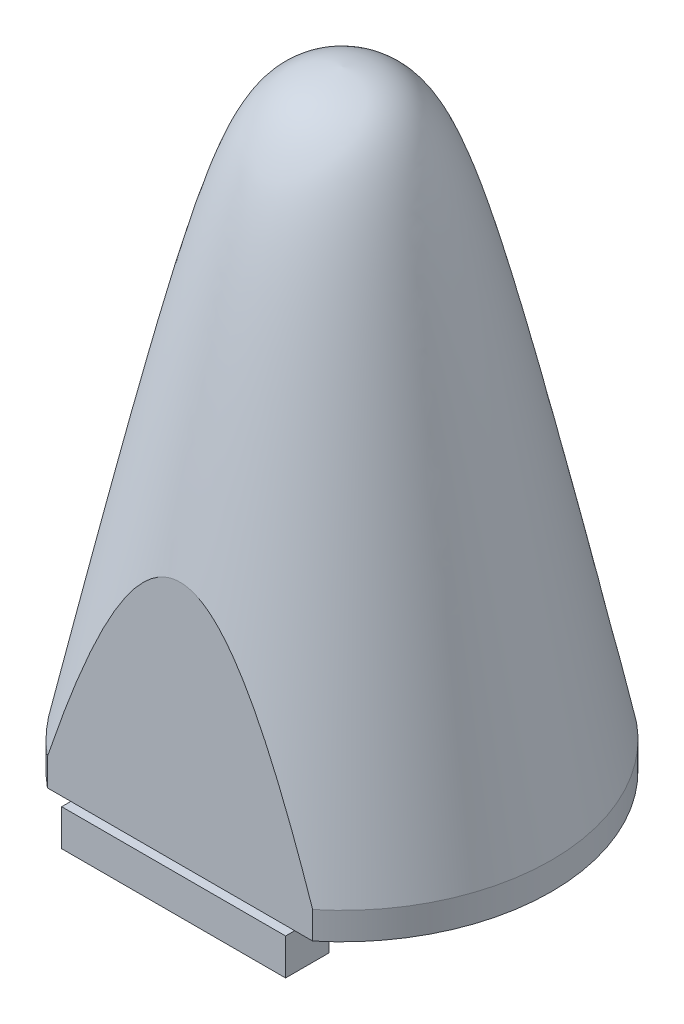
SolidWorks part; units mm, degrees
ref_plane "前视基准面" through (0, 0, 0) normal (0, 0, 1) x (1, 0, 0)
ref_plane "上视基准面" through (0, 0, 0) normal (0, 1, 0) x (1, 0, 0)
ref_plane "右视基准面" through (0, 0, 0) normal (1, 0, 0) x (0, 0, -1)
sketch "草图2" plane through (0, 0, 0) normal (0, 0, 1) x (1, 0, 0)
  line L1 (0, 0) -> (-11.5, 0)
  line L2 (0, 0) -> (0, 32)
  conic Q0 (0, 32) -> (-11.5, 0) control (-4.7103, 31.6151) rho 0.718414
  dimension "D1" = 11.5
  dimension "D2" = 32
revolve "旋转1" add sketch "草图2" angle 360 about L2
sketch "草图3" plane through (0, 0, 0) normal (0, 0, 1) x (1, 0, 0)
  line L0 (0, 31) -> (0, 0)
  line L1 (-11.5, 0) -> (11.5, 0) construction
  line L2 (0, 0) -> (-8, 0)
  line L3 (-8, 0) -> (0, 31)
  point P5 (-8, 0)
  point P8 (0, 31)
  dimension "D1" = 8
  dimension "D2" = 31
revolve "切除-旋转1" cut sketch "草图3" angle 360 about L0
sketch "草图4" plane through (0, 0, 0) normal (0, 1, 0) x (1, 0, 0)
  circle A0 centre (0, 0) radius 11.5
  dimension "D1" = 23
extrude "凸台-拉伸1" add sketch "草图4" against normal blind 1.5
sketch "草图5" plane through (0, -1.5, 0) normal (0, -1, 0) x (1, 0, 0)
  line L0 (-9.6096, 0) -> (10.8151, 0) construction
  line L9 (-7.6853, -7.4312) -> (8.2673, 7.9939) construction
  line L10 (4.3011, 6.4) -> (4.3011, 5.02)
  line L11 (-8, -6.4) -> (-8, 6.4)
  line L12 (-8, 6.4) -> (-6.6189, 6.4)
  line L14 (-6.6189, -6.4) -> (-8, -6.4)
  line L15 (-6.6189, 6.4) -> (4.3011, 6.4)
  line L16 (0, 0) -> (6.5976, -7.5148) construction
  line L17 (4.3011, 5.02) -> (-6.5, 5.02)
  line L18 (-6.5, 5.02) -> (-6.5, -5.02)
  line L19 (4.3011, -6.4) -> (4.3011, -5.02)
  line L20 (4.3011, -5.02) -> (-6.5, -5.02)
  line L21 (-6.6189, -6.4) -> (4.3011, -6.4)
  circle A1 centre (0, 0) radius 11.5 construction
  point P0 (0, 0)
  point P1 (0, 0)
  point P14 (-8, 0)
  point P23 (-6.5, 0)
  dimension "D1" = 6.4
  dimension "D2" = 8
  dimension "D3" = 10.92
  dimension "D4" = 1.38
  dimension "D5" = 1.5
extrude "凸台-拉伸2" add sketch "草图5" along normal blind 4
sketch "草图8" plane through (0, -1.5, 0) normal (0, -1, 0) x (-1, 0, 0)
  line L0 (10.5002, -4.69) -> (10.5002, 4.69)
  line L1 (7.285, -8.8982) -> (-7.285, -8.8982)
  line L2 (0, 0) -> (-4.2231, 0) construction
  line L5 (7.285, 8.8982) -> (-7.285, 8.8982)
  circle A0 centre (0, 0) radius 11.5 construction
  arc A2 (-7.285, -8.8982) -> (7.285, -8.8982) centre (0, 0) ccw
  arc A3 (10.5002, 4.69) -> (10.5002, -4.69) centre (0, 0) cw
  arc A5 (-7.285, 8.8982) -> (7.285, 8.8982) centre (0, 0) cw
  dimension "D1" = 9.38
  dimension "D2" = 14.57
sketch "草图6" plane through (0, -1.5, 0) normal (0, -1, 0) x (1, 0, 0)
  line L1 (0, 0) -> (11.7815, 0) construction
sketch "草图7" plane through (0, -1.5, 0) normal (0, -1, 0) x (1, 0, 0)
  line L1 (6.5, -5.02) -> (-6.5, -5.02)
  line L2 (6.5, -5.02) -> (6.5, 5.02)
  line L3 (6.5, 5.02) -> (-6.5, 5.02)
  line L4 (-6.5, -5.02) -> (-6.5, 5.02)
  line L5 (6.5, -5.02) -> (-6.5, 5.02) construction
  line L6 (6.5, 5.02) -> (-6.5, -5.02) construction
  point P0 (0, 0)
extrude "切除-拉伸3" cut sketch "草图7" against normal blind 2
extrude "切除-拉伸4" cut sketch "草图8" against normal through all
sketch "草图9" plane through (0, 0, 6.4) normal (0, 0, 1) x (1, 0, 0)
  line L0 (4.3011, -5.5) -> (4.3011, -1.5) construction
  line L1 (-8, -5.5) -> (4.3011, -5.5)
  line L2 (-8, -5.5) -> (-8, -3.5)
  line L3 (-8, -3.5) -> (4.3011, -3.5)
  line L4 (4.3011, -5.5) -> (4.3011, -3.5)
extrude "凸台-拉伸3" add sketch "草图9" along normal blind 1
sketch "草图10" plane through (0, 0, -6.4) normal (0, 0, -1) x (-1, 0, 0)
  line L0 (8, -5.5) -> (8, -1.5) construction
  line L1 (-4.3011, -5.5) -> (8, -5.5)
  line L2 (-4.3011, -5.5) -> (-4.3011, -3.5)
  line L3 (-4.3011, -3.5) -> (8, -3.5)
  line L4 (8, -5.5) -> (8, -3.5)
extrude "凸台-拉伸4" add sketch "草图10" along normal blind 1
